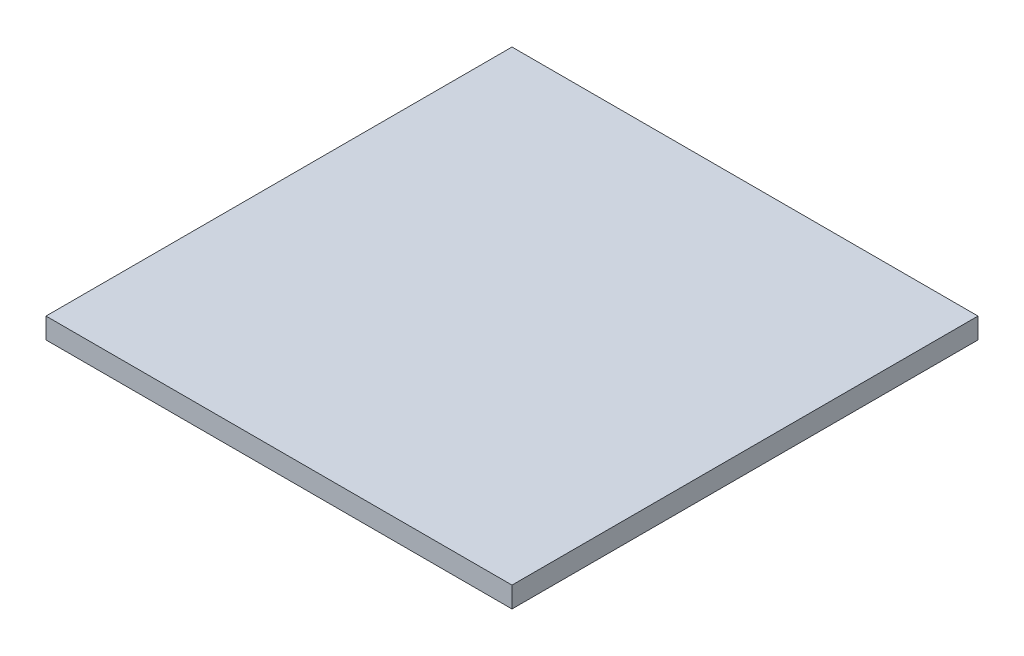
SolidWorks part; units mm, degrees
ref_plane "Plan de face" through (0, 0, 0) normal (0, 0, 1) x (1, 0, 0)
ref_plane "Plan de dessus" through (0, 0, 0) normal (0, 1, 0) x (1, 0, 0)
ref_plane "Plan de droite" through (0, 0, 0) normal (1, 0, 0) x (0, 0, -1)
sketch "Esquisse1" plane through (0, 0, 0) normal (0, 1, 0) x (1, 0, 0)
  line L1 (0, 0) -> (45, 0)
  line L2 (0, 0) -> (0, 45)
  line L3 (0, 45) -> (45, 45)
  line L4 (45, 0) -> (45, 45)
extrude "Boss.-Extru.1" add sketch "Esquisse1" along normal blind 2
